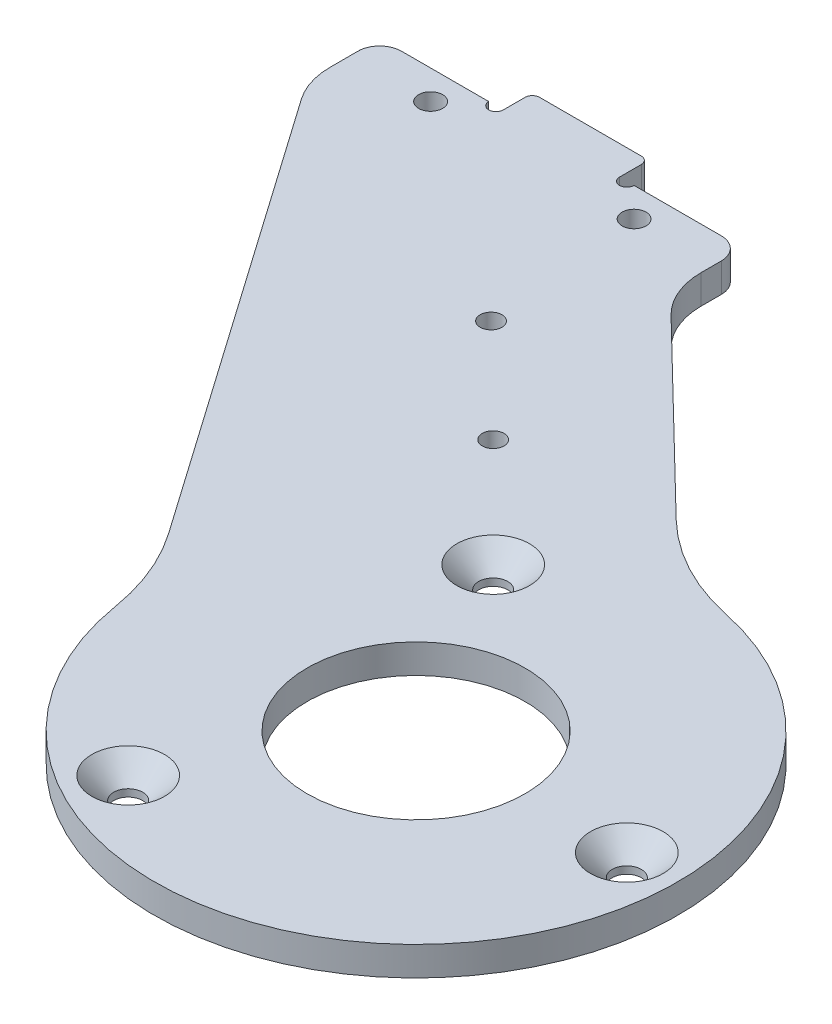
SolidWorks part; units mm, degrees
material "Thornel Mat VMA"
ref_plane "前视基准面" through (0, 0, 0) normal (0, 0, 1) x (1, 0, 0)
ref_plane "上视基准面" through (0, 0, 0) normal (0, 1, 0) x (1, 0, 0)
ref_plane "右视基准面" through (0, 0, 0) normal (1, 0, 0) x (0, 0, -1)
sketch "草图1" plane through (0, 0, 0) normal (0, 1, 0) x (1, 0, 0)
  line L0 (-46.0918, 2.5735) -> (107.1195, 22.8576) construction
  line L1 (-85, 80) -> (-35, 80)
  line L2 (101.4093, -246.5221) -> (869.4093, -246.5221) construction
  line L3 (-35, 80) -> (-35, 70)
  line L4 (-85, 80) -> (-85, 70)
  line L5 (-85, 70) -> (-36, 0)
  line L6 (0, 0) -> (-109.1595, 0) construction
  line L7 (0, 0) -> (0, 75.0483) construction
  line L8 (0, 0) -> (81.4628, 0) construction
  line L9 (0, 0) -> (0, -69.3688) construction
  line L10 (0, 36) -> (-35, 70)
  line L11 (-60, 80) -> (-60, -8.6185) construction
  line L12 (-60, 80) -> (0, 0) construction
  arc A0 (-36, 0) -> (0, 36) centre (0, 0) ccw
  circle A1 centre (0, 0) radius 36 construction
  arc A2 (0, 36) -> (-36, 0) centre (0, 0) ccw construction
  circle A3 centre (0, 0) radius 36 construction
  dimension "D6" = 36
  dimension "D1" = 50
  dimension "D2" = 60
  dimension "D3" = 10
  dimension "D4" = 10
  dimension "D5" = 80
extrude "凸台-拉伸1" add sketch "草图1" along normal blind 4
fillet "圆角1" radius 30 1 edges at (0, 2, -36)
fillet "圆角2" radius 30 1 edges at (-36, 2, 0)
sketch "草图4" plane through (0, 4, 0) normal (0, 1, 0) x (1, 0, 0)
  line L0 (-60, 80) -> (-60, 15.697) construction
  line L1 (-35, 80) -> (-85, 80) construction
  circle A0 centre (-46, 76) radius 1.65
  circle A1 centre (-74, 76) radius 1.65
  dimension "D1" = 28
  dimension "D2" = 3.3
  dimension "D3" = 4
extrude "切除-拉伸3" cut sketch "草图4" against normal blind 4
fillet "圆角4" radius 10 2 edges at (-85, 2, -70) (-35, 2, -70)
fillet "圆角5" radius 3 2 edges at (-85, 2, -80) (-35, 2, -80)
sketch "草图7" plane through (0, 4, 0) normal (0, 1, 0) x (1, 0, 0)
  line L0 (-60, 80) -> (-60, 94.9774) construction
  line L1 (-38, 80) -> (-82, 80) construction
  line L3 (-68, 84) -> (-52, 84)
  line L4 (-68, 84) -> (-68, 80)
  line L5 (-68, 80) -> (-52, 80)
  line L6 (-52, 84) -> (-52, 80)
  line L7 (-60, 80) -> (-60, 84) construction
  line L8 (-68, 82) -> (-52, 82) construction
  point P4 (-60, 82)
  dimension "D1" = 4
  dimension "D2" = 16
extrude "凸台-拉伸3" add sketch "草图7" against normal blind 4
sketch "草图8" plane through (0, 4, 0) normal (0, 1, 0) x (1, 0, 0)
  line L1 (-50, 80) -> (-52, 80)
  line L2 (-60, 84) -> (-60, 22.1698) construction
  line L3 (-52, 84) -> (-68, 84) construction
  line L4 (-70, 80) -> (-68, 80)
  arc A1 (-52, 80) -> (-50, 80) centre (-51, 80) ccw
  arc A2 (-68, 80) -> (-70, 80) centre (-69, 80) cw
  dimension "D1" = 1
extrude "切除-拉伸5" cut sketch "草图8" against normal blind 4
fillet "圆角7" radius 1 2 edges at (-68, 2, -84) (-52, 2, -84)
sketch "草图9" plane through (0, 4, 0) normal (0, 1, 0) x (1, 0, 0)
  circle A0 centre (0, 0) radius 15
  dimension "D1" = 30
extrude "切除-拉伸6" cut sketch "草图9" against normal blind 10
sketch "草图10" plane through (0, 0, 0) normal (0, -1, 0) x (1, 0, 0)
  line L0 (0, 36) -> (0, -47.5197) construction
  line L1 (0, 0) -> (49.6251, 0) construction
  arc A0 (7.4395, -35.2229) -> (-35.5233, 5.8392) centre (0, 0) ccw construction
  circle A1 centre (0, 0) radius 29 construction
  circle A2 centre (29, 0) radius 2
  circle A3 centre (-14.5, -25.1147) radius 2
  circle A4 centre (-14.5, 25.1147) radius 2
  dimension "D1" = 58
  dimension "D2" = 4
  dimension "D3" = 3
extrude "切除-拉伸7" cut sketch "草图10" against normal blind 10
chamfer "倒角1" distance 3 angle 45 3 edges at (-14.5, 4, 27.1147) (29, 4, 2) (-14.5, 4, -23.1147)
sketch "草图11" plane through (0, 4, 0) normal (0, 1, 0) x (1, 0, 0)
  circle A0 centre (-29.4012, 40.0071) radius 1.2 construction
  circle A1 centre (-43.6869, 54.0042) radius 1.2 construction
  circle A2 centre (-29.4012, 40.0071) radius 1.2
  circle A3 centre (-43.6869, 54.0042) radius 1.2
extrude "切除-拉伸8" cut sketch "草图11" against normal blind 10
sketch "草图12" plane through (0, 4, 0) normal (0, 1, 0) x (1, 0, 0)
  circle A0 centre (-43.6869, 54.0042) radius 1.5
  circle A1 centre (-29.4012, 40.0071) radius 1.5
  dimension "D1" = 3
  dimension "D2" = 3
extrude "切除-拉伸9" cut sketch "草图12" against normal blind 10
